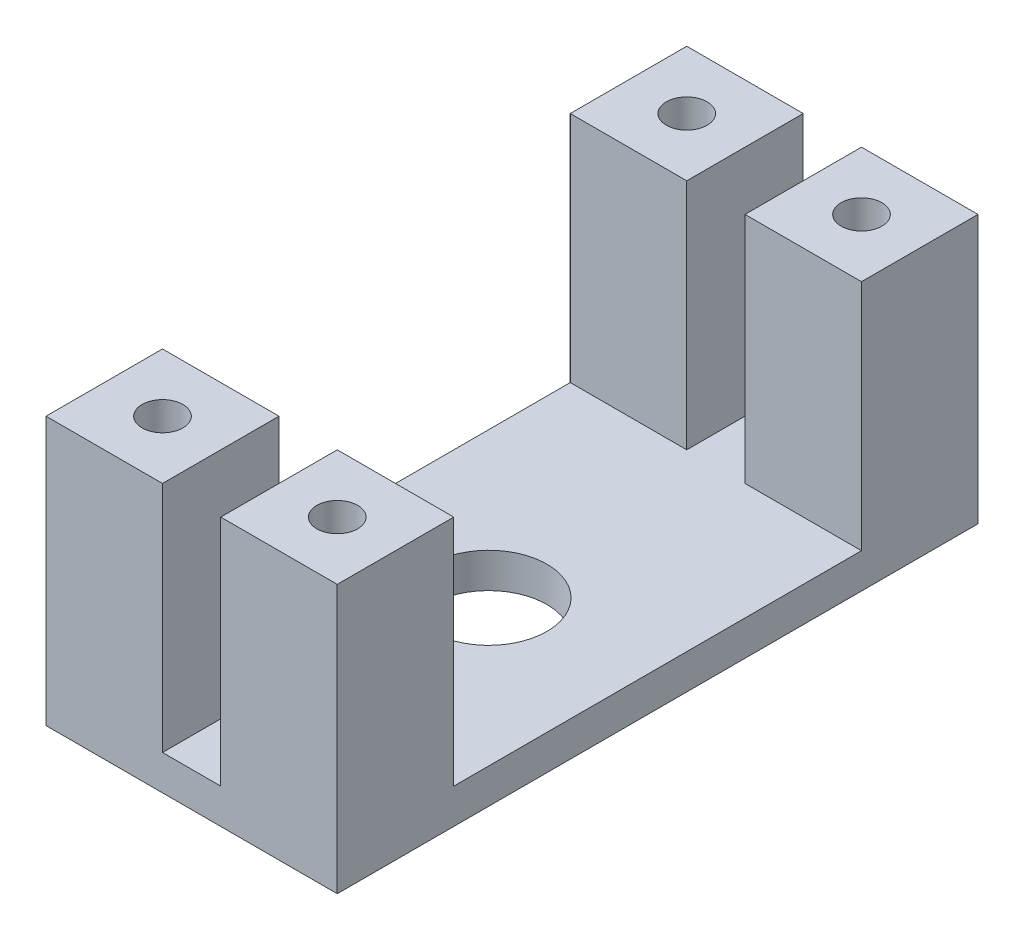
SolidWorks part; units mm, degrees
material "AISI 304"
ref_plane "前视基准面" through (0, 0, 0) normal (0, 0, 1) x (1, 0, 0)
ref_plane "上视基准面" through (0, 0, 0) normal (0, 1, 0) x (1, 0, 0)
ref_plane "右视基准面" through (0, 0, 0) normal (1, 0, 0) x (0, 0, -1)
sketch "草图1" plane through (0, 0, 0) normal (0, 1, 0) x (1, 0, 0)
  line L1 (-12.5, 27.5) -> (12.5, 27.5)
  line L2 (-12.5, 27.5) -> (-12.5, -27.5)
  line L3 (-12.5, -27.5) -> (12.5, -27.5)
  line L4 (12.5, 27.5) -> (12.5, -27.5)
  line L5 (-12.5, 27.5) -> (12.5, -27.5) construction
  line L6 (-12.5, -27.5) -> (12.5, 27.5) construction
  point P0 (0, 0)
  dimension "D1" = 55
  dimension "D2" = 25
extrude "凸台-拉伸1" add sketch "草图1" along normal blind 3
sketch "草图2" plane through (0, 3, 0) normal (0, 1, 0) x (1, 0, 0)
  line L0 (-12.5, 27.5) -> (-2.5, 17.5)
  line L1 (-12.5, 27.5) -> (-2.5, 27.5)
  line L2 (-12.5, 27.5) -> (-12.5, 17.5)
  line L3 (-12.5, 17.5) -> (-2.5, 17.5)
  line L4 (-2.5, 27.5) -> (-2.5, 17.5)
  line L5 (12.5, 27.5) -> (2.5, 27.5)
  line L6 (12.5, 27.5) -> (12.5, 17.5)
  line L7 (12.5, 17.5) -> (2.5, 17.5)
  line L8 (2.5, 27.5) -> (2.5, 17.5)
  line L9 (-12.5, -27.5) -> (-2.5, -27.5)
  line L10 (-12.5, -27.5) -> (-12.5, -17.5)
  line L11 (-12.5, -17.5) -> (-2.5, -17.5)
  line L12 (-2.5, -27.5) -> (-2.5, -17.5)
  line L13 (12.5, -27.5) -> (2.5, -27.5)
  line L14 (12.5, -27.5) -> (12.5, -17.5)
  line L15 (12.5, -17.5) -> (2.5, -17.5)
  line L16 (2.5, -27.5) -> (2.5, -17.5)
  line L17 (12.5, 27.5) -> (2.5, 17.5)
  line L18 (-12.5, -27.5) -> (-2.5, -17.5)
  line L19 (12.5, -27.5) -> (2.5, -17.5)
  line L20 (0, 0) -> (0, 2)
  line L21 (0, 0) -> (0, -2)
  dimension "D1" = 10
  dimension "D2" = 10
  dimension "D3" = 10
  dimension "D4" = 10
  dimension "D5" = 10
  dimension "D6" = 10
  dimension "D7" = 10
  dimension "D8" = 10
  dimension "D9" = 2
  dimension "D10" = 2
sketch "草图5" plane through (0, 3, 0) normal (0, 1, 0) x (1, 0, 0)
  point P0 (0, 0)
  point P4 (0, -2)
sketch "草图7" plane through (0, 3, 0) normal (0, 1, 0) x (1, 0, 0)
  line L1 (-12.5, 27.5) -> (-2.5, 27.5)
  line L2 (-12.5, 27.5) -> (-12.5, 17.5)
  line L3 (-12.5, 17.5) -> (-2.5, 17.5)
  line L4 (-2.5, 27.5) -> (-2.5, 17.5)
  line L5 (2.5, 27.5) -> (12.5, 27.5)
  line L6 (2.5, 27.5) -> (2.5, 17.5)
  line L7 (2.5, 17.5) -> (12.5, 17.5)
  line L8 (12.5, 27.5) -> (12.5, 17.5)
  line L9 (12.5, -27.5) -> (2.5, -27.5)
  line L10 (12.5, -27.5) -> (12.5, -17.5)
  line L11 (12.5, -17.5) -> (2.5, -17.5)
  line L12 (2.5, -27.5) -> (2.5, -17.5)
  line L13 (-12.5, -27.5) -> (-2.5, -27.5)
  line L14 (-12.5, -27.5) -> (-12.5, -17.5)
  line L15 (-12.5, -17.5) -> (-2.5, -17.5)
  line L16 (-2.5, -27.5) -> (-2.5, -17.5)
extrude "凸台-拉伸2" add sketch "草图7" along normal blind 20
hole_wizard "孔2" positions "草图5" profile "草图6" legacy
sketch "草图6" plane through (0, 3, 2) normal (1, 0, 0) x (0, 0, 1)
  line L0 (0, 0) -> (0, 3)
  line L1 (0, 3) -> (5, 3)
  line L2 (5, 3) -> (5, 0)
  line L3 (5, 0) -> (0, 0)
  line L4 (0, 110) -> (0, -10) construction
  dimension "直径" = 10
  dimension "深度" = 3
sketch "草图3" plane through (0, 3, 0) normal (0, 1, 0) x (1, 0, 0)
  line L0 (-12.5, 27.5) -> (-2.5, 17.5) construction
  line L1 (12.5, 27.5) -> (2.5, 17.5) construction
  line L2 (12.5, -27.5) -> (2.5, -17.5) construction
  line L3 (-12.5, -27.5) -> (-2.5, -17.5) construction
  point P0 (-7.5, 22.5)
  point P4 (7.5, 22.5)
  point P8 (7.5, -22.5)
  point P12 (-7.5, -22.5)
hole_wizard "孔1" positions "草图3" profile "草图4" legacy
sketch "草图4" plane through (-7.5, 3, -22.5) normal (1, 0, 0) x (0, 0, 1)
  line L0 (0, 0) -> (0, 3)
  line L1 (0, 3) -> (1.75, 3)
  line L2 (1.75, 3) -> (1.75, 0)
  line L3 (1.75, 0) -> (0, 0)
  line L4 (0, 110) -> (0, -10) construction
  dimension "直径" = 3.5
  dimension "深度" = 3
sketch "草图8" plane through (0, 0, 0) normal (0, -1, 0) x (-1, 0, 0)
  line L0 (12.5, 27.5) -> (2.5, 17.5) construction
  line L1 (-12.5, 27.5) -> (-2.5, 17.5) construction
  line L2 (-12.5, -27.5) -> (-2.5, -17.5) construction
  line L3 (12.5, -27.5) -> (2.5, -17.5) construction
  point P0 (7.5, 22.5)
  point P4 (-7.5, 22.5)
  point P8 (-7.5, -22.5)
  point P12 (7.5, -22.5)
hole_wizard "孔3" positions "草图8" profile "草图9" legacy end condition through all
sketch "草图9" plane through (-7.5, 0, -22.5) normal (1, 0, 0) x (0, 0, -1)
  line L0 (0, 0) -> (0, 23)
  line L1 (0, 23) -> (1.75, 23)
  line L2 (1.75, 23) -> (1.75, 0)
  line L3 (1.75, 0) -> (0, 0)
  line L4 (0, 110) -> (0, -10) construction
  dimension "直径" = 3.5
  dimension "深度" = 23
